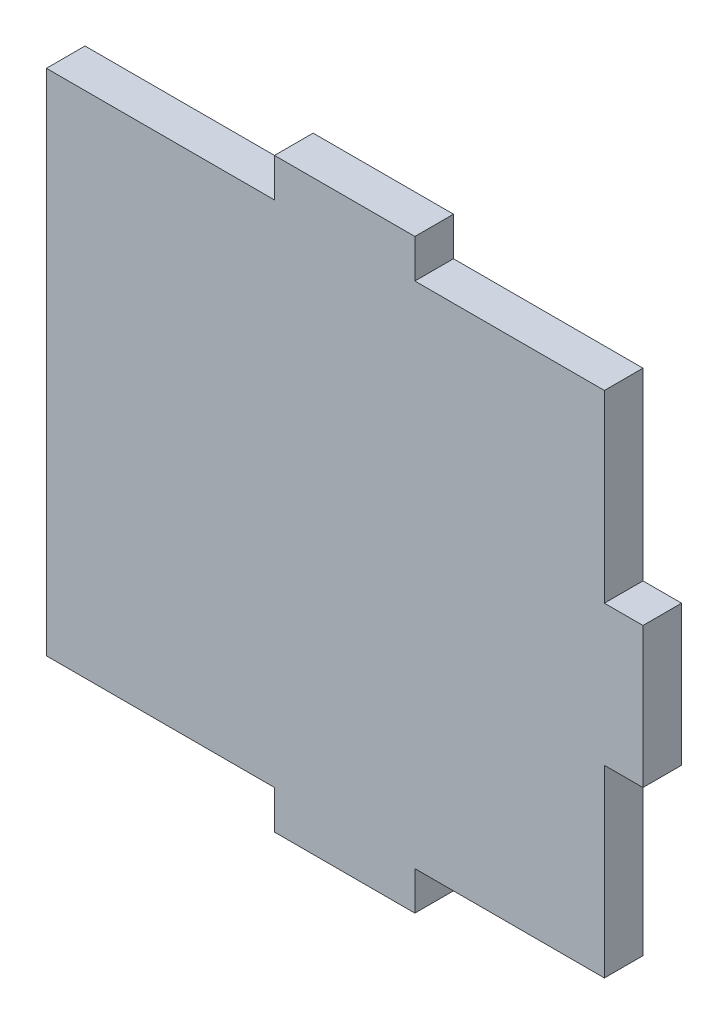
SolidWorks part; units mm, degrees
ref_plane "Alzado" through (0, 0, 0) normal (0, 0, 1) x (1, 0, 0)
ref_plane "Planta" through (0, 0, 0) normal (0, 1, 0) x (1, 0, 0)
ref_plane "Vista lateral" through (0, 0, 0) normal (1, 0, 0) x (0, 0, -1)
sketch "Croquis1" plane through (0, 0, 0) normal (0, 0, 1) x (1, 0, 0)
  line L0 (-65.4922, -11.8855) -> (-32.9922, -11.8855)
  line L1 (-65.4922, 60.6145) -> (-32.9922, 60.6145)
  line L2 (-65.4922, 60.6145) -> (-65.4922, -11.8855)
  line L3 (-12.9922, -11.8855) -> (14.0078, -11.8855)
  line L4 (14.0078, 60.6145) -> (14.0078, 34.3645)
  line L5 (-22.9922, -17.3855) -> (-12.9922, -17.3855)
  line L6 (-12.9922, -17.3855) -> (-12.9922, -11.8855)
  line L7 (14.0078, 14.3645) -> (19.5078, 14.3645)
  line L8 (-32.9922, -11.8855) -> (-32.9922, -17.3855)
  line L9 (-32.9922, -17.3855) -> (-22.9922, -17.3855)
  line L10 (14.0078, 14.3645) -> (14.0078, -11.8855)
  line L11 (-12.9922, 60.6145) -> (14.0078, 60.6145)
  line L12 (-22.9922, 66.1145) -> (-12.9922, 66.1145)
  line L13 (14.0078, 34.3645) -> (19.5078, 34.3645)
  line L14 (19.5078, 34.3645) -> (19.5078, 14.3645)
  line L15 (-12.9922, 66.1145) -> (-12.9922, 60.6145)
  line L16 (14.0078, 34.3645) -> (14.0078, 14.3645) construction
  line L17 (-32.9922, 60.6145) -> (-32.9922, 66.1145)
  line L18 (-32.9922, 66.1145) -> (-22.9922, 66.1145)
  dimension "D1" = 5.5
  dimension "D2" = 78
  dimension "D3" = 26.25
  dimension "D4" = 26.25
  dimension "D5" = 5.5
  dimension "D6" = 79.5
extrude "Saliente-Extruir1" add sketch "Croquis1" along normal blind 5.5
